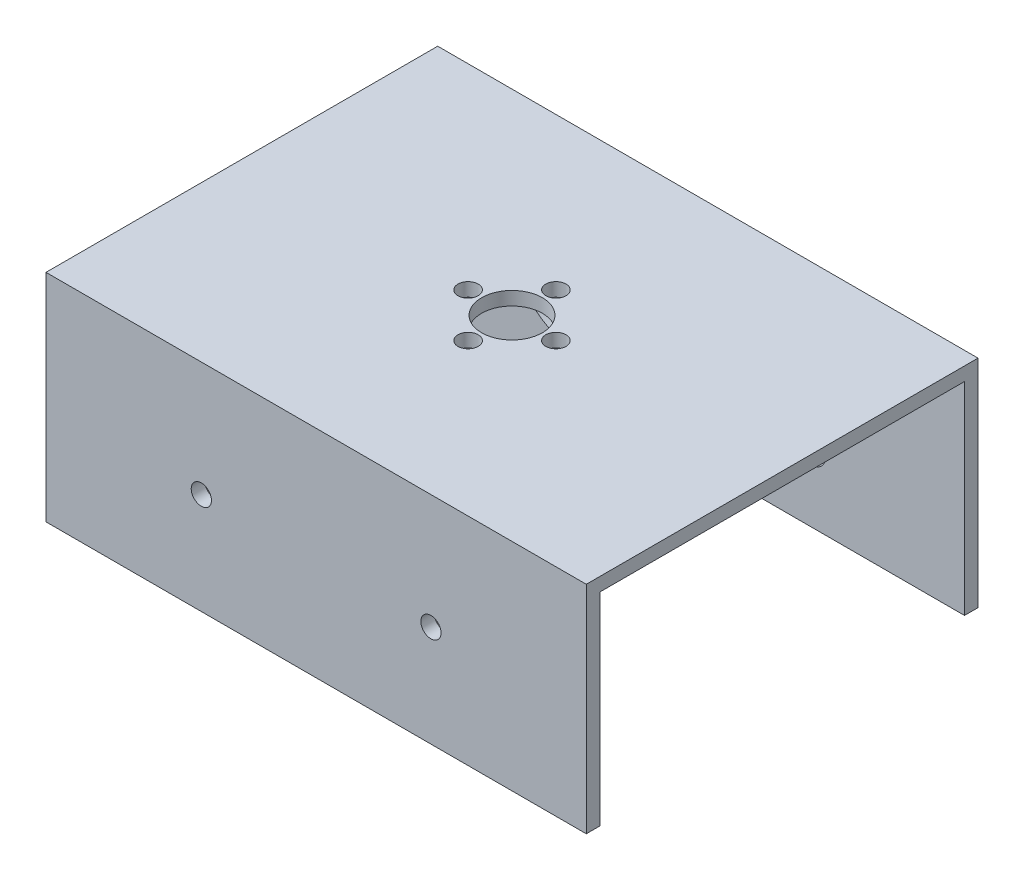
SolidWorks part; units mm, degrees
ref_plane "前视基准面" through (0, 0, 0) normal (0, 0, 1) x (1, 0, 0)
ref_plane "上视基准面" through (0, 0, 0) normal (0, 1, 0) x (1, 0, 0)
ref_plane "右视基准面" through (0, 0, 0) normal (1, 0, 0) x (0, 0, -1)
sketch "草图1" plane through (0, 0, 0) normal (0, 0, 1) x (1, 0, 0)
  line L1 (-40, -15) -> (40, -15)
  line L2 (-40, -15) -> (-40, 15)
  line L3 (-40, 15) -> (40, 15)
  line L4 (40, -15) -> (40, 15)
  line L5 (-40, -15) -> (40, 15) construction
  line L6 (-40, 15) -> (40, -15) construction
  point P0 (0, 0)
  dimension "D1" = 80
  dimension "D2" = 30
extrude "凸台-拉伸1" add sketch "草图1" along normal blind 2
sketch "草图2" plane through (0, 15, 0) normal (0, 1, 0) x (1, 0, 0)
  line L0 (-40, -2) -> (-40, 56)
  line L1 (-40, 56) -> (40, 56)
  line L2 (40, 56) -> (40, -2)
  line L4 (40, 0) -> (-40, 0)
  line L5 (-40, 0) -> (-40, -2)
  line L6 (-40, -2) -> (40, -2)
  line L7 (40, -2) -> (40, 0)
  line L10 (-40, -2) -> (40, -2)
  dimension "D2" = 58
  dimension "D1" = 0
extrude "凸台-拉伸2" add sketch "草图2" along normal blind 2
sketch "草图3" plane through (0, 15, 0) normal (0, -1, 0) x (1, 0, 0)
  line L0 (-40, -56) -> (40, -56)
  line L1 (40, -56) -> (40, -54)
  line L2 (40, 0) -> (40, -56) construction
  line L3 (40, -54) -> (-40, -54)
  line L4 (-40, -56) -> (-40, 0) construction
  line L5 (-40, -54) -> (-40, -56)
  dimension "D1" = 2
extrude "凸台-拉伸3" add sketch "草图3" along normal blind 30
sketch "草图5" plane through (0, 17, 0) normal (0, 1, 0) x (1, 0, 0)
  line L0 (-40, 27) -> (40, 27) construction
  line L1 (-40, 56) -> (-40, -2) construction
  line L2 (40, -2) -> (40, 56) construction
  line L3 (0, 56) -> (0, -2) construction
  line L4 (40, 56) -> (-40, 56) construction
  line L5 (-40, -2) -> (40, -2) construction
  circle A0 centre (0, 27) radius 4.5
  circle A1 centre (0, 27) radius 6.5 construction
  circle A2 centre (-6.5, 27) radius 1.5
  circle A3 centre (6.5, 27) radius 1.5
  circle A4 centre (0, 33.5) radius 1.5
  circle A5 centre (0, 20.5) radius 1.5
  dimension "D1" = 9
  dimension "D2" = 13
  dimension "D3" = 3
  dimension "D4" = 3
  dimension "D5" = 3
  dimension "D6" = 3
extrude "切除-拉伸1" cut sketch "草图5" against normal up to next
sketch "草图6" plane through (0, 0, -56) normal (0, 0, -1) x (-1, 0, 0)
  line L0 (-28.8431, 0) -> (27.4504, 0) construction
  circle A0 centre (-17, 0) radius 1.5
  circle A1 centre (17, 0) radius 1.5
  dimension "D1" = 3
  dimension "D2" = 3
  dimension "D3" = 17
  dimension "17" = 17
extrude "切除-拉伸3" cut sketch "草图6" against normal up to surface (58 mm away) up to face at (0, 1, 2)
sketch "草图7" plane through (0, 0, -56) normal (0, 0, -1) x (-1, 0, 0)
  circle A0 centre (17, 0) radius 10
  dimension "D1" = 20
extrude "切除-拉伸4" cut sketch "草图7" against normal up to next contours A0
sketch "草图8" plane through (0, 0, -54) normal (0, 0, 1) x (1, 0, 0)
  line L0 (40, -15) -> (40, 17) construction
  line L1 (-40, 17) -> (40, 17) construction
  circle A0 centre (17.42, 5) radius 2
  circle A1 centre (17.42, -5) radius 2
  dimension "D3" = 4
  dimension "D6" = 4
  dimension "D1" = 22.58
  dimension "D2" = 12
  dimension "D4" = 22.58
  dimension "D5" = 10
extrude "切除-拉伸5" cut sketch "草图8" against normal up to next
sketch "草图9" plane through (0, 0, -54) normal (0, 0, 1) x (1, 0, 0)
  line L0 (-40, 17) -> (40, 17) construction
  line L1 (-40, 17) -> (-40, -15) construction
  circle A0 centre (-32.07, 5) radius 2
  circle A1 centre (-32.07, -5) radius 2
  dimension "D5" = 4
  dimension "D6" = 4
  dimension "D1" = 12
  dimension "D2" = 7.93
  dimension "D3" = 7.93
  dimension "D4" = 10
extrude "切除-拉伸6" cut sketch "草图9" against normal up to next
